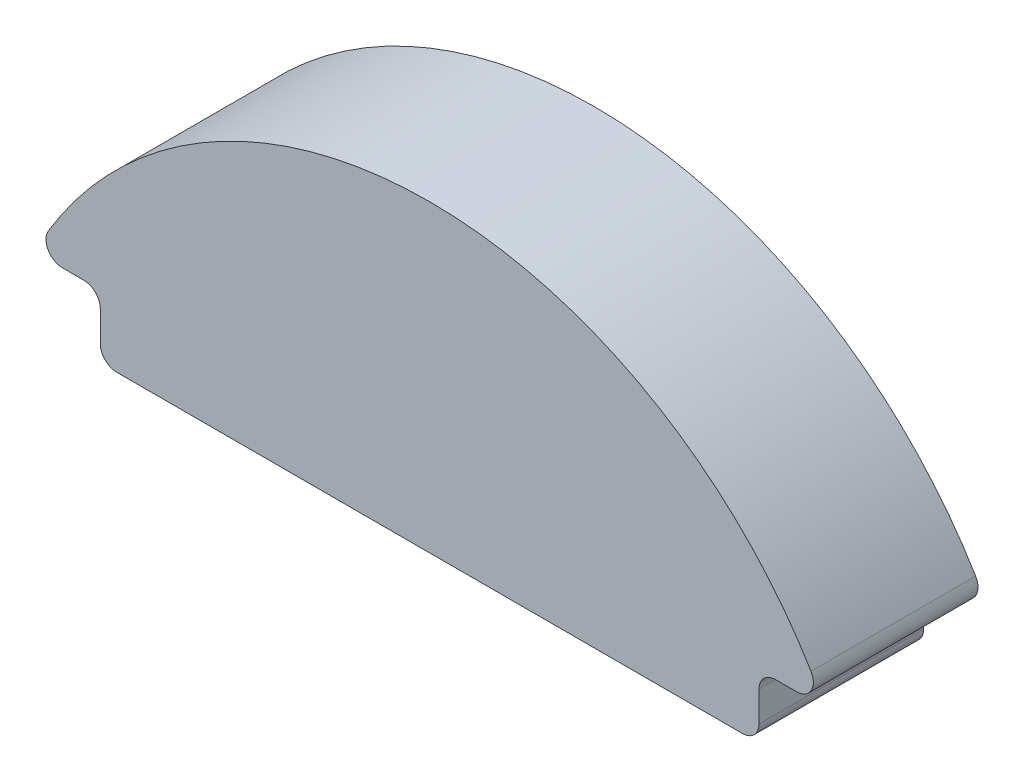
SolidWorks part; units mm, degrees
ref_plane "Plan de face" through (0, 0, 0) normal (0, 0, 1) x (1, 0, 0)
ref_plane "Plan de dessus" through (0, 0, 0) normal (0, 1, 0) x (1, 0, 0)
ref_plane "Plan de droite" through (0, 0, 0) normal (1, 0, 0) x (0, 0, -1)
sketch "Esquisse1" plane through (0, 0, 0) normal (0, 0, 1) x (1, 0, 0)
  line L0 (-79.1101, 0) -> (110.8899, 0)
  line L1 (-84.1101, 5) -> (-84.1101, 14.2)
  line L2 (-89.1101, 19.2) -> (-95.6069, 19.2)
  line L3 (115.8899, 5) -> (115.8899, 14.2)
  line L4 (120.8899, 19.2) -> (127.3867, 19.2)
  arc A0 (-99.8952, 26.771) -> (131.675, 26.771) centre (15.8899, -42.6466) cw
  arc A1 (127.3867, 19.2) -> (131.675, 26.771) centre (127.3867, 24.2) ccw
  arc A2 (115.8899, 14.2) -> (120.8899, 19.2) centre (120.8899, 14.2) cw
  arc A3 (110.8899, 0) -> (115.8899, 5) centre (110.8899, 5) ccw
  arc A4 (-79.1101, 0) -> (-84.1101, 5) centre (-79.1101, 5) cw
  arc A5 (-84.1101, 14.2) -> (-89.1101, 19.2) centre (-89.1101, 14.2) ccw
  arc A6 (-95.6069, 19.2) -> (-99.8952, 26.771) centre (-95.6069, 24.2) cw
  point P10 (135.8899, 19.2)
  point P13 (115.8899, 19.2)
  point P16 (115.8899, 0)
  point P19 (-84.1101, 0)
  point P22 (-84.1101, 19.2)
  point P25 (-104.1101, 19.2)
  dimension "D6" = 135
  dimension "D7" = 5
  dimension "D1" = 20
  dimension "D2" = 20
  dimension "D3" = 200
  dimension "D4" = 19.2
  dimension "D5" = 19.2
extrude "Boss.-Extru.1" add sketch "Esquisse1" along normal blind 50
shell "Coque1" thickness 2
